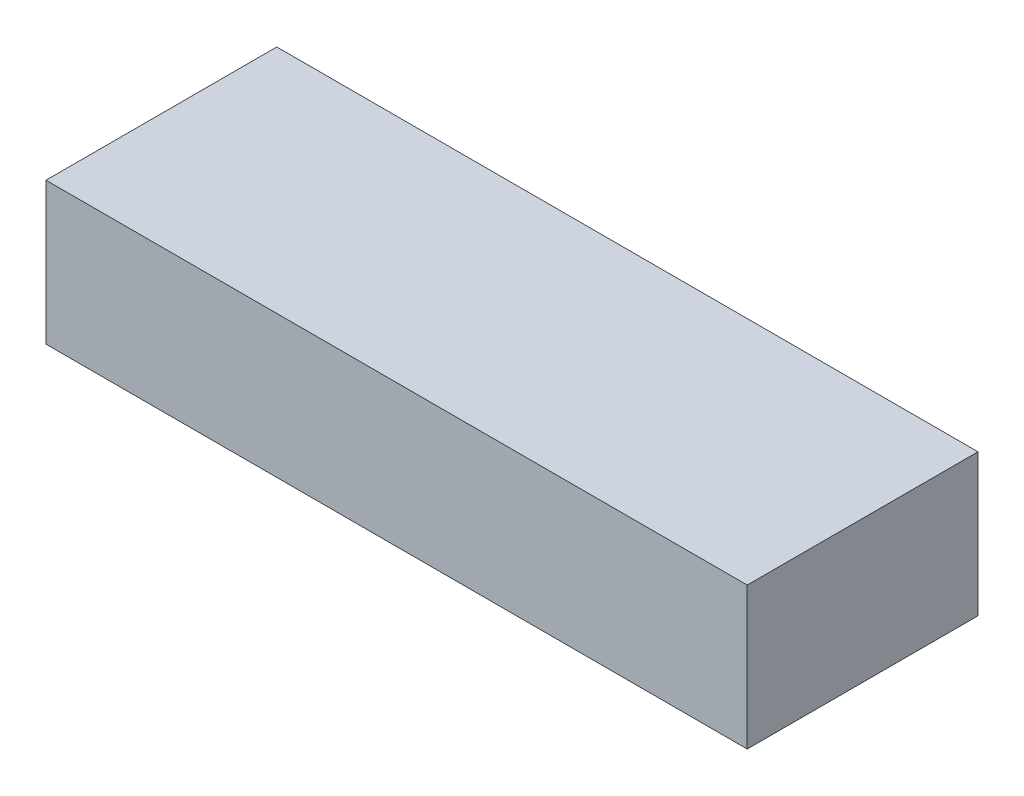
SolidWorks part; units mm, degrees
ref_plane "Front Plane" through (0, 0, 0) normal (0, 0, 1) x (1, 0, 0)
ref_plane "Top Plane" through (0, 0, 0) normal (0, 1, 0) x (1, 0, 0)
ref_plane "Right Plane" through (0, 0, 0) normal (1, 0, 0) x (0, 0, -1)
sketch "Sketch1" plane through (0, 0, 0) normal (0, 1, 0) x (1, 0, 0)
  line L1 (-118.5, -39) -> (118.5, -39)
  line L2 (-118.5, -39) -> (-118.5, 39)
  line L3 (-118.5, 39) -> (118.5, 39)
  line L4 (118.5, -39) -> (118.5, 39)
  line L5 (-118.5, -39) -> (118.5, 39) construction
  line L6 (-118.5, 39) -> (118.5, -39) construction
  point P0 (0, 0)
  dimension "D1" = 237
  dimension "D2" = 78
extrude "Boss-Extrude1" add sketch "Sketch1" along normal blind 48
